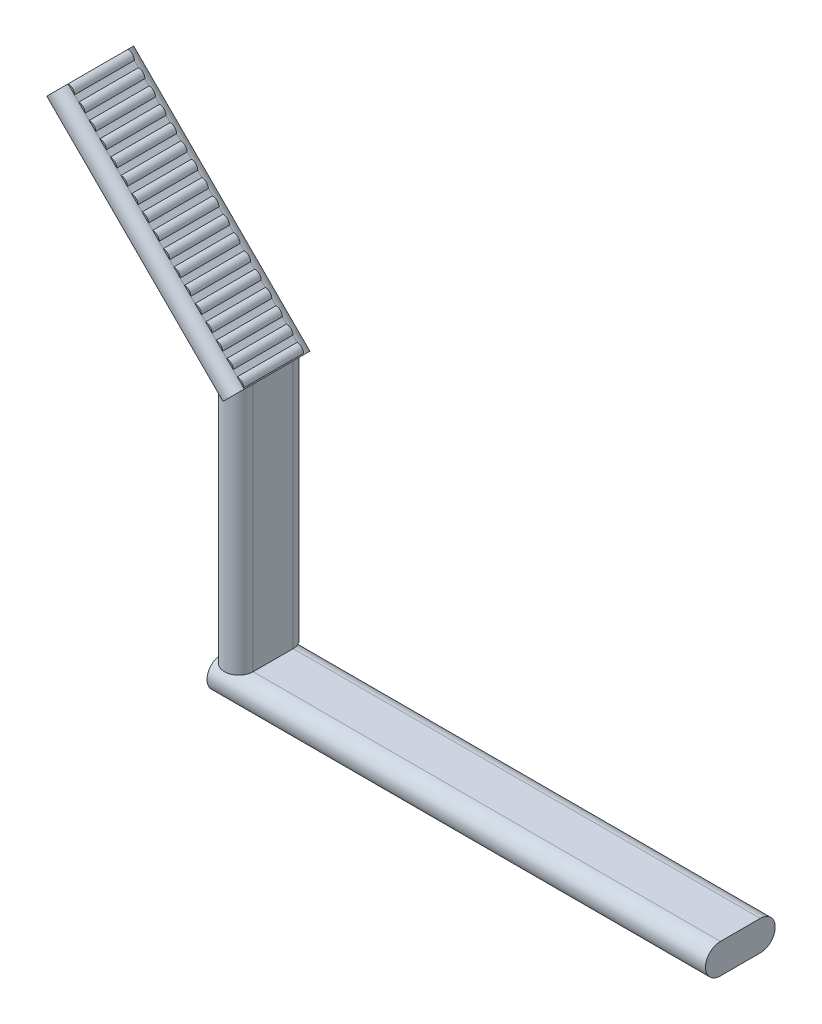
SolidWorks part; units mm, degrees
material "5052-O"
ref_plane "Front Plane" through (0, 0, 0) normal (0, 0, 1) x (1, 0, 0)
ref_plane "Top Plane" through (0, 0, 0) normal (0, 1, 0) x (1, 0, 0)
ref_plane "Right Plane" through (0, 0, 0) normal (1, 0, 0) x (0, 0, -1)
sketch "Sketch1" plane through (0, 0, 0) normal (1, 0, 0) x (0, 0, -1)
  line L0 (-10, 0) -> (10, 0) construction
  line L1 (-10, 7.5) -> (10, 7.5)
  line L2 (-10, -7.5) -> (10, -7.5)
  arc A0 (-10, 7.5) -> (-10, -7.5) centre (-10, 0) ccw
  arc A1 (10, -7.5) -> (10, 7.5) centre (10, 0) ccw
  point P2 (0, 0)
  dimension "D1" = 15
  dimension "D2" = 20
extrude "Boss-Extrude1" add sketch "Sketch1" along normal blind 250
sketch "Sketch11" plane through (0, 7.5, 0) normal (0, 1, 0) x (1, 0, 0)
  line L0 (8.4471, -10) -> (8.4471, 10) construction
  line L1 (250, -10) -> (0, -10) construction
  line L2 (250, 10) -> (0, 10) construction
  line L3 (1.2208, -10) -> (1.2208, 10)
  line L4 (15.6733, -10) -> (15.6733, 10)
  line L5 (0, 10) -> (0, -10) construction
  line L6 (8.4471, 0) -> (0, 0) construction
  arc A0 (1.2208, -10) -> (15.6733, -10) centre (8.4471, -10) ccw
  arc A1 (15.6733, 10) -> (1.2208, 10) centre (8.4471, 10) ccw
  point P6 (8.4471, 0)
extrude "Boss-Extrude6" add sketch "Sketch11" along normal blind 125
ref_plane "Plane2" through (-58.4133, 58.4133, 0) normal (0.7071, -0.7071, 0) x (-0.7071, -0.7071, 0)
sketch "Sketch12" plane through (-58.4133, 58.4133, 0) normal (0.7071, -0.7071, 0) x (-0.7071, -0.7071, 0)
  line L0 (-100.0226, -15) -> (-100.0226, 15) construction
  line L1 (-105.5681, -15) -> (-105.5681, 15)
  line L2 (-94.477, -15) -> (-94.477, 15)
  line L3 (0, 0) -> (-100.0226, 0) construction
  arc A0 (-105.5681, -15) -> (-94.477, -15) centre (-100.0226, -15) ccw
  arc A1 (-94.477, 15) -> (-105.5681, 15) centre (-100.0226, 15) ccw
  point P2 (-100.0226, 0)
  dimension "D1" = 15
extrude "Boss-Extrude7" add sketch "Sketch12" against normal blind 125
ref_plane "Plane3" through (0, 0, 15) normal (0, 0, 1) x (0.7071, -0.7071, 0)
sketch "Sketch13" plane through (0, 0, 15) normal (0, 0, 1) x (0.7071, -0.7071, 0)
  line L0 (-207.609, 105.5681) -> (-82.609, 105.5681) construction
  line L1 (-207.609, 105.5681) -> (-203.0794, 105.5681)
  line L2 (-200.109, 105.5681) -> (-195.5794, 105.5681)
  line L3 (-192.609, 105.5681) -> (-188.0794, 105.5681)
  line L4 (-185.109, 105.5681) -> (-180.5794, 105.5681)
  line L5 (-177.609, 105.5681) -> (-173.0794, 105.5681)
  line L6 (-170.109, 105.5681) -> (-165.5794, 105.5681)
  line L7 (-162.609, 105.5681) -> (-158.0794, 105.5681)
  line L8 (-155.109, 105.5681) -> (-150.5794, 105.5681)
  line L9 (-147.609, 105.5681) -> (-143.0794, 105.5681)
  line L10 (-140.109, 105.5681) -> (-135.5794, 105.5681)
  line L11 (-132.609, 105.5681) -> (-128.0794, 105.5681)
  line L12 (-125.109, 105.5681) -> (-120.5794, 105.5681)
  line L13 (-117.609, 105.5681) -> (-113.0794, 105.5681)
  line L14 (-110.109, 105.5681) -> (-105.5794, 105.5681)
  line L15 (-102.609, 105.5681) -> (-98.0794, 105.5681)
  line L16 (-95.109, 105.5681) -> (-90.5794, 105.5681)
  line L17 (-87.609, 105.5681) -> (-83.0794, 105.5681)
  arc A0 (-207.609, 105.5681) -> (-203.0794, 105.5681) centre (-205.3442, 103.3033) cw
  arc A1 (-200.109, 105.5681) -> (-195.5794, 105.5681) centre (-197.8442, 103.3033) cw
  arc A2 (-192.609, 105.5681) -> (-188.0794, 105.5681) centre (-190.3442, 103.3033) cw
  arc A3 (-185.109, 105.5681) -> (-180.5794, 105.5681) centre (-182.8442, 103.3033) cw
  arc A4 (-177.609, 105.5681) -> (-173.0794, 105.5681) centre (-175.3442, 103.3033) cw
  arc A5 (-170.109, 105.5681) -> (-165.5794, 105.5681) centre (-167.8442, 103.3033) cw
  arc A6 (-162.609, 105.5681) -> (-158.0794, 105.5681) centre (-160.3442, 103.3033) cw
  arc A7 (-155.109, 105.5681) -> (-150.5794, 105.5681) centre (-152.8442, 103.3033) cw
  arc A8 (-147.609, 105.5681) -> (-143.0794, 105.5681) centre (-145.3442, 103.3033) cw
  arc A9 (-140.109, 105.5681) -> (-135.5794, 105.5681) centre (-137.8442, 103.3033) cw
  arc A10 (-132.609, 105.5681) -> (-128.0794, 105.5681) centre (-130.3442, 103.3033) cw
  arc A11 (-125.109, 105.5681) -> (-120.5794, 105.5681) centre (-122.8442, 103.3033) cw
  arc A12 (-117.609, 105.5681) -> (-113.0794, 105.5681) centre (-115.3442, 103.3033) cw
  arc A13 (-110.109, 105.5681) -> (-105.5794, 105.5681) centre (-107.8442, 103.3033) cw
  arc A14 (-102.609, 105.5681) -> (-98.0794, 105.5681) centre (-100.3442, 103.3033) cw
  arc A15 (-95.109, 105.5681) -> (-90.5794, 105.5681) centre (-92.8442, 103.3033) cw
  arc A16 (-87.609, 105.5681) -> (-83.0794, 105.5681) centre (-85.3442, 103.3033) cw
  dimension "D1" = 17
extrude "Boss-Extrude8" add sketch "Sketch13" against normal blind 30
